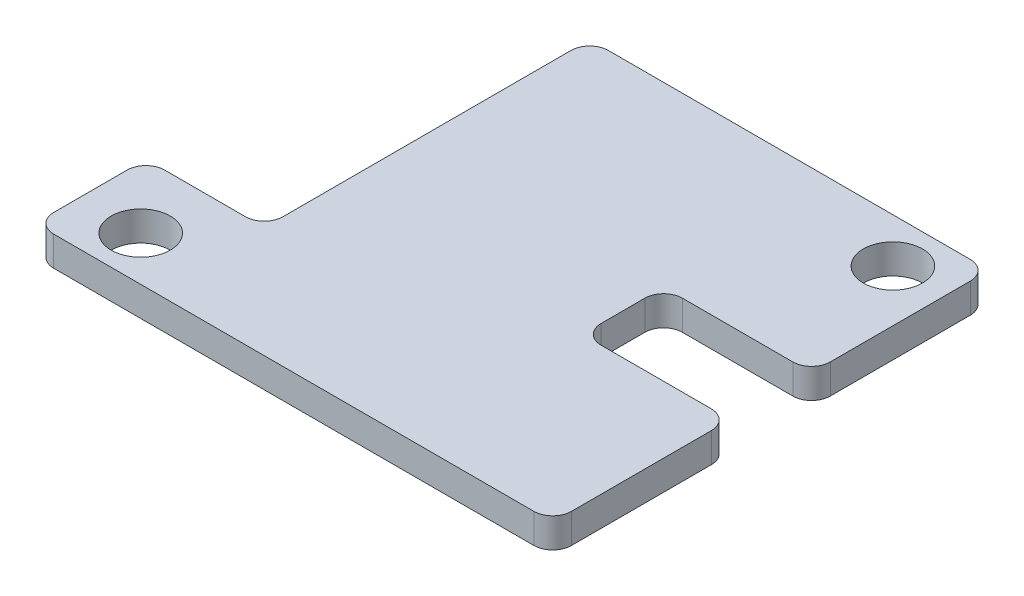
SolidWorks part; units mm, degrees
material "aluminio"
ref_plane "Alzado" through (0, 0, 0) normal (0, 0, 1) x (1, 0, 0)
ref_plane "Planta" through (0, 0, 0) normal (0, 1, 0) x (1, 0, 0)
ref_plane "Vista lateral" through (0, 0, 0) normal (1, 0, 0) x (0, 0, -1)
sketch "Croquis1" plane through (0, 0, 0) normal (0, 1, 0) x (1, 0, 0)
  line L0 (0, 0) -> (35, 0)
  line L1 (0, 0) -> (0, 7.5)
  line L2 (8, 29.5) -> (35, 29.5)
  line L3 (35, 0) -> (35, 12)
  line L6 (35, 17.5) -> (25, 17.5)
  line L7 (8, 29.5) -> (8, 7.5)
  line L8 (8, 7.5) -> (0, 7.5)
  line L10 (25, 17.5) -> (25, 12)
  line L11 (25, 12) -> (35, 12)
  line L12 (35, 17.5) -> (35, 29.5)
  circle A0 centre (4.15, 3) radius 2
  circle A1 centre (31.5, 26.5) radius 2
  dimension "D3" = 4
  dimension "D2" = 29.5
  dimension "D4" = 4.15
  dimension "D5" = 3
  dimension "D6" = 27.35
  dimension "D7" = 23.5
  dimension "D8" = 8
  dimension "D9" = 35
  dimension "D10" = 7.5
  dimension "D11" = 25
  dimension "D13" = 12
  dimension "D14" = 12
extrude "Saliente-Extruir1" add sketch "Croquis1" along normal blind 2
sketch "Croquis2" plane through (0, 0, 0) normal (0, -1, 0) x (1, 0, 0)
  line L1 (35, -29.5) -> (0, -29.5)
  line L2 (35, -29.5) -> (35, 0)
  line L3 (35, 0) -> (0, 0)
  line L4 (0, -29.5) -> (0, 0)
  circle A0 centre (31.5, -26.5) radius 2 construction
  circle A1 centre (4.15, -3) radius 2 construction
  circle A2 centre (31.5, -26.5) radius 2
  circle A3 centre (4.15, -3) radius 2
extrude "Saliente-Extruir2" [suppressed] add sketch "Croquis2" along normal blind 0.2
other "Mover cara1" [suppressed] parameters "D1"=0.1
sketch "Croquis3" [suppressed] plane through (0, 0, 0) normal (0, 1, 0) x (1, 0, 0)
  line L0 (8, 7.5) -> (0, 7.5) construction
  line L1 (0, 29.5) -> (3.5, 29.5)
  line L2 (0, 29.5) -> (0, 7.5)
  line L3 (0, 7.5) -> (3.5, 7.5)
  line L4 (3.5, 29.5) -> (3.5, 7.5)
  dimension "D1" = 3.5
extrude "Saliente-Extruir3" [suppressed] add sketch "Croquis3" along normal up to surface (1.9 mm away)
other "Mover cara2" [suppressed] parameters "D1"=1
sketch "Croquis4" [suppressed] plane through (0, 0.1, 0) normal (0, 1, 0) x (1, 0, 0)
  line L0 (3.5, 7.5) -> (3.5, 29.5) construction
  line L1 (16, 29.5) -> (3.5, 29.5)
  line L2 (16, 29.5) -> (16, 27.5)
  line L3 (16, 27.5) -> (3.5, 27.5)
  line L4 (3.5, 29.5) -> (3.5, 27.5)
  dimension "D1" = 2
extrude "Saliente-Extruir4" [suppressed] add sketch "Croquis4" along normal up to surface (1 mm away)
fillet "Redondeo1" [suppressed] radius 0.75
fillet "Redondeo4" [suppressed] radius 2
fillet "Redondeo5" radius 1.27 10 edges at (0, 1, 0) (35, 1, -29.5) (25, 1, -17.5) (25, 1, -12) (8, 1, -29.5) (8, 1, -7.5) (0, 1, -7.5) (35, 1, 0) (35, 1, -12) (35, 1, -17.5)
